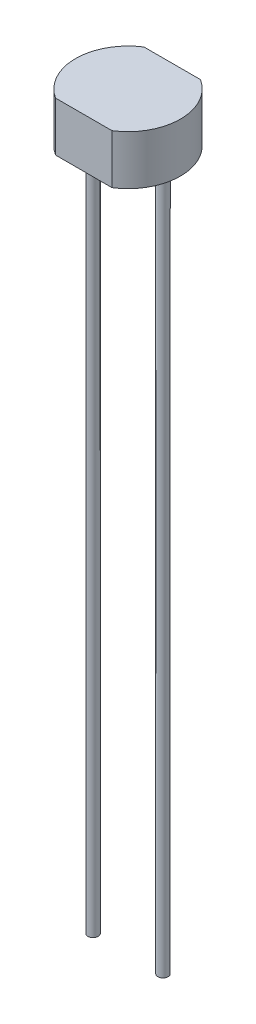
SolidWorks part; units mm, degrees
ref_plane "Front Plane" through (0, 0, 0) normal (0, 0, 1) x (1, 0, 0)
ref_plane "Top Plane" through (0, 0, 0) normal (0, 1, 0) x (1, 0, 0)
ref_plane "Right Plane" through (0, 0, 0) normal (1, 0, 0) x (0, 0, -1)
sketch "Sketch1" plane through (0, 0, 0) normal (0, 1, 0) x (1, 0, 0)
  line L1 (2.55, 2.15) -> (-2.55, 2.15)
  line L2 (2.55, 2.15) -> (2.55, -2.15)
  line L3 (2.55, -2.15) -> (-2.55, -2.15)
  line L4 (-2.55, 2.15) -> (-2.55, -2.15)
  line L5 (2.55, 2.15) -> (-2.55, -2.15) construction
  line L6 (2.55, -2.15) -> (-2.55, 2.15) construction
  circle A0 centre (0, 0) radius 2.55
  dimension "D1" = 5.1
  dimension "D2" = 4.3
  dimension "D3" = 5.1
extrude "Boss-Extrude1" add sketch "Sketch1" along normal blind 2.4 contours L3 A0 L1
sketch "Sketch2" plane through (0, 0, 0) normal (0, -1, 0) x (1, 0, 0)
  line L0 (-2.55, 0) -> (2.55, 0) construction
  arc A0 (-1.3711, 2.15) -> (-1.3711, -2.15) centre (0, 0) ccw construction
  arc A1 (1.3711, -2.15) -> (1.3711, 2.15) centre (0, 0) ccw construction
  circle A2 centre (-1.7, 0) radius 0.25
  circle A3 centre (1.7, 0) radius 0.25
  dimension "D1" = 0.5
  dimension "D2" = 0.5
  dimension "D3" = 3.4
  dimension "D4" = 1.7
extrude "Boss-Extrude2" add sketch "Sketch2" along normal blind 34 contours A3 | A2
